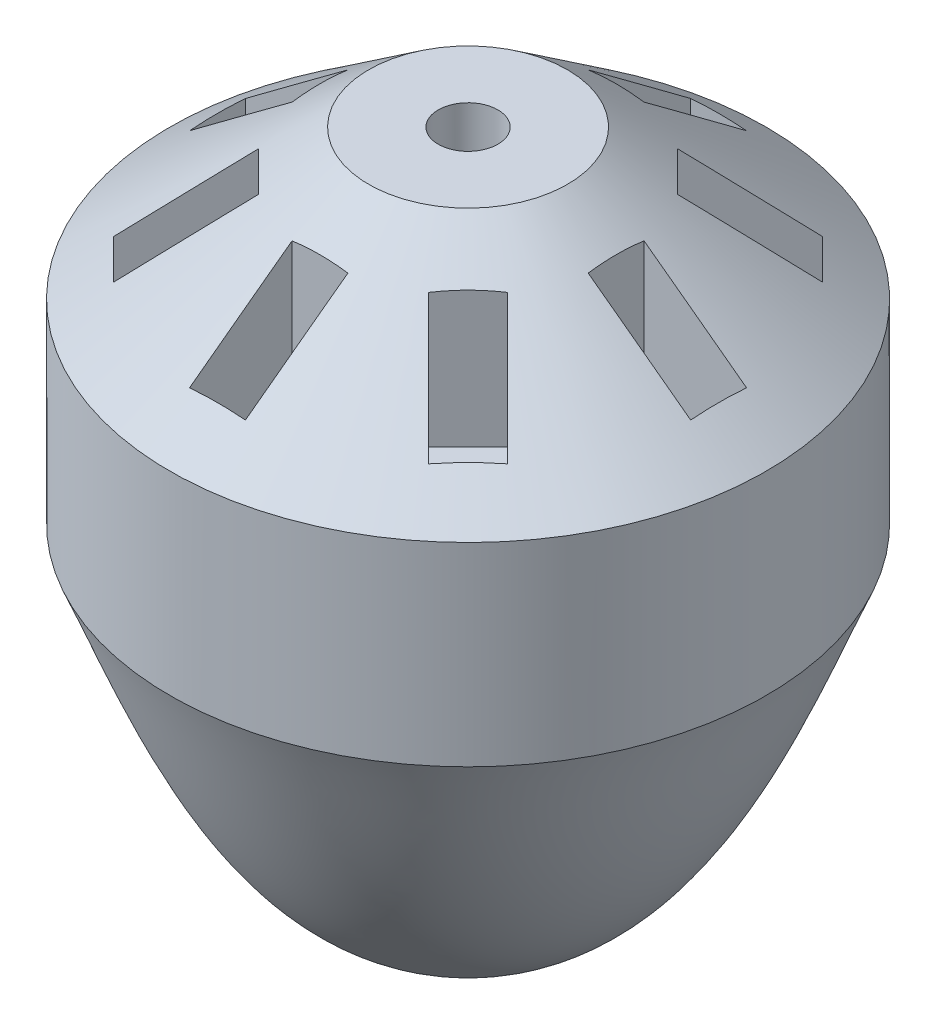
SolidWorks part; units mm, degrees
material "黄铜"
ref_plane "前视基准面" through (0, 0, 0) normal (0, 0, 1) x (1, 0, 0)
ref_plane "上视基准面" through (0, 0, 0) normal (0, 1, 0) x (1, 0, 0)
ref_plane "右视基准面" through (0, 0, 0) normal (1, 0, 0) x (0, 0, -1)
sketch "草图1" plane through (0, 0, 0) normal (0, 0, 1) x (1, 0, 0)
  line L0 (-1000, 0.1826) -> (-35, 0.1826) construction
  line L1 (0, 0) -> (0, 5.3837) construction
  line L2 (-15, 0.1826) -> (-5, 7.6802)
  line L3 (-5, 7.6802) -> (0, 7.6802)
  line L4 (-15, 0.1826) -> (-15, -3.5696)
  line L7 (0, -9.5937) -> (0, 7.6802)
  line L13 (0, -9.5937) -> (0, -26.7914)
  line L24 (-15, -6.0696) -> (-15, -9.5937)
  line L25 (-15, 0.1826) -> (0, 0.1826) construction
  line L26 (-15, -3.5696) -> (-15, -6.0696)
  spline S0 degree 3 poles (0, -26.7914) (-8.8903, -27.787) (-12.5676, -15.3479) (-15, -9.5937) knots 0 0 0 0 1 1 1 1
  point P4 (0, 0)
  point P24 (-35, 25.8293)
  point P27 (-40, 25.8293)
  dimension "D2" = 5
revolve "旋转3" add sketch "草图1" angle 360 about L7
sketch "草图3" plane through (0, 0, 0) normal (0, 1, 0) x (1, 0, 0)
  circle A0 centre (0, 0) radius 1.5
  dimension "D1" = 3
extrude "切除-拉伸1" cut sketch "草图3" against normal blind 1 and the other way blind 10
sketch "草图4" plane through (0, 0, 0) normal (0, 1, 0) x (1, 0, 0)
  line L0 (0, 0) -> (0, 20.8552) construction
  line L1 (-1.4056, 12.6069) -> (-1.4056, 7.4508)
  line L2 (-1.4056, 12.6069) -> (1.4056, 12.6069)
  line L3 (-1.4056, 7.4508) -> (1.4056, 7.4508)
  line L4 (1.4056, 12.6069) -> (1.4056, 7.4508)
  line L5 (-1.4056, 12.6069) -> (1.4056, 7.4508) construction
  line L6 (-1.4056, 7.4508) -> (1.4056, 12.6069) construction
  point P3 (0, 10.0288)
extrude "切除-拉伸2" cut sketch "草图4" against normal blind 1 and the other way through all
pattern_circular "阵列(圆周)1" count 8 every 45 about axis through (0, 0, 0) along (0, 1, 0) of "切除-拉伸2"
sketch "草图5" plane through (0, 0, 0) normal (0, 0, 1) x (1, 0, 0)
